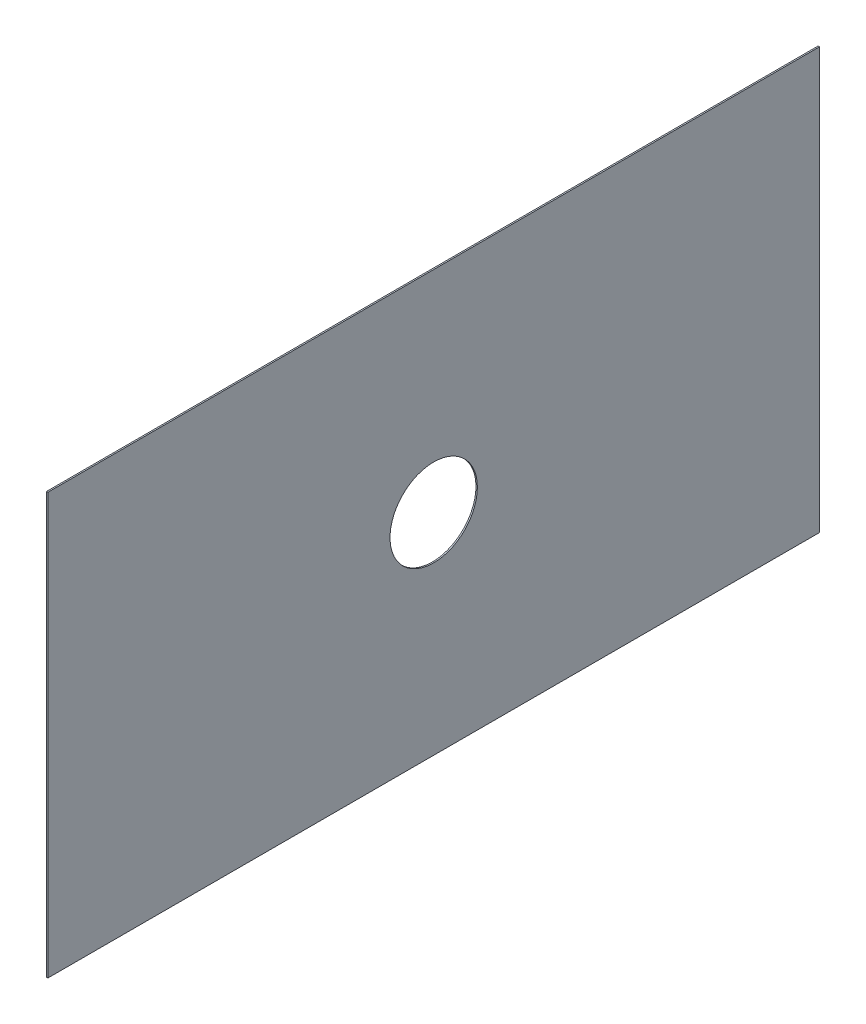
SolidWorks part; units mm, degrees
ref_plane "Alzado" through (0, 0, 0) normal (0, 0, 1) x (1, 0, 0)
ref_plane "Planta" through (0, 0, 0) normal (0, 1, 0) x (1, 0, 0)
ref_plane "Vista lateral" through (0, 0, 0) normal (1, 0, 0) x (0, 0, -1)
sketch "Croquis1" plane through (0, 0, 0) normal (1, 0, 0) x (0, 0, -1)
  line L1 (552, -301) -> (-552, -301)
  line L2 (552, -301) -> (552, 301)
  line L3 (552, 301) -> (-552, 301)
  line L4 (-552, -301) -> (-552, 301)
  line L5 (552, -301) -> (-552, 301) construction
  line L6 (552, 301) -> (-552, -301) construction
  point P0 (0, 0)
  dimension "D1" = 602
  dimension "D2" = 1104
extrude "Extruir1" add sketch "Croquis1" along normal blind 2
sketch "Croquis2" plane through (2, 0, 0) normal (1, 0, 0) x (0, 0, -1)
  circle A0 centre (0, 0) radius 62.5
  dimension "D1" = 125
extrude "Extruir2" cut sketch "Croquis2" against normal blind 2
